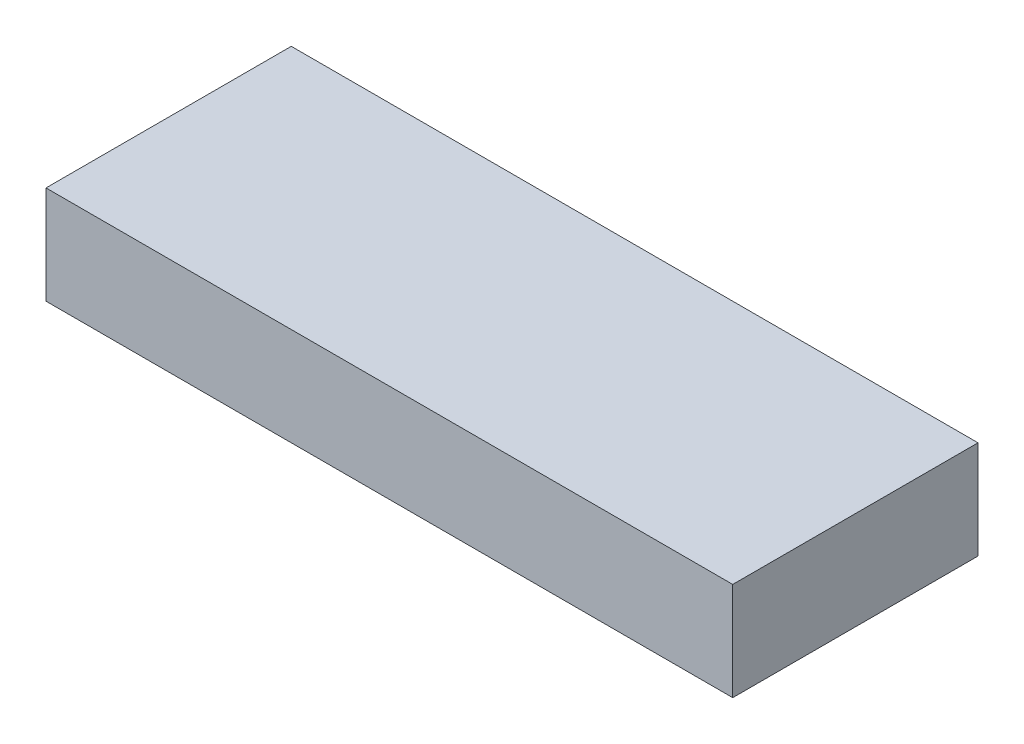
SolidWorks part; units mm, degrees
ref_plane "Front Plane" through (0, 0, 0) normal (0, 0, 1) x (1, 0, 0)
ref_plane "Top Plane" through (0, 0, 0) normal (0, 1, 0) x (1, 0, 0)
ref_plane "Right Plane" through (0, 0, 0) normal (1, 0, 0) x (0, 0, -1)
sketch "Sketch1" plane through (0, 0, 0) normal (0, 1, 0) x (1, 0, 0)
  line L1 (-44.45, -15.875) -> (44.45, -15.875)
  line L2 (-44.45, -15.875) -> (-44.45, 15.875)
  line L3 (-44.45, 15.875) -> (44.45, 15.875)
  line L4 (44.45, -15.875) -> (44.45, 15.875)
  line L5 (-44.45, -15.875) -> (44.45, 15.875) construction
  line L6 (-44.45, 15.875) -> (44.45, -15.875) construction
  point P0 (0, 0)
  dimension "D1" = 88.9
  dimension "D2" = 31.75
extrude "Boss-Extrude1" add sketch "Sketch1" along normal blind 12.7
sketch "Sketch2" plane through (-44.45, 0, 0) normal (-1, 0, 0) x (0, 0, 1)
  line L0 (15.875, 12.7) -> (15.875, 0) construction
  line L1 (15.875, 12.7) -> (15.875, 0) construction
  circle A0 centre (0, 6.35) radius 4.7625
  dimension "D1" = 9.525
  dimension "D2" = 6.35
  dimension "D3" = 12.7
extrude "Boss-Extrude2" [suppressed] add sketch "Sketch2" along normal blind 57.15
equation "\"D2@Sketch2\"=\"D3@Sketch2\"/2"
